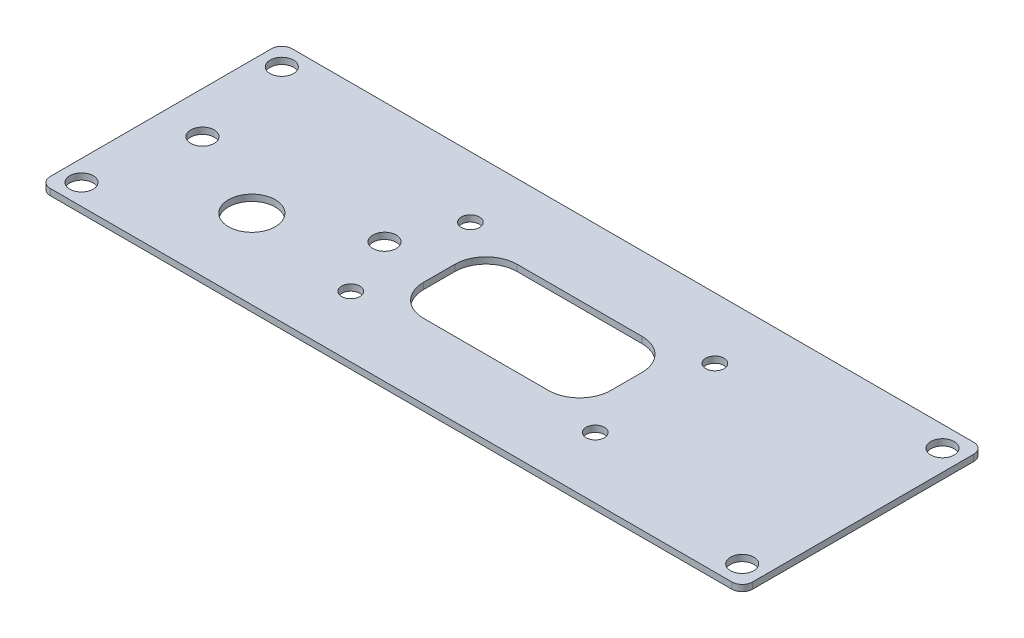
SolidWorks part; units mm, degrees
material "1023 Carbon Steel Sheet (SS)"
ref_plane "Front Plane" through (0, 0, 0) normal (0, 0, 1) x (1, 0, 0)
ref_plane "Top Plane" through (0, 0, 0) normal (0, 1, 0) x (1, 0, 0)
ref_plane "Right Plane" through (0, 0, 0) normal (1, 0, 0) x (0, 0, -1)
sketch "BASE" plane through (0, 0, 0) normal (0, 1, 0) x (1, 0, 0)
  line L0 (63.5, 19.25) -> (-63.5, 19.25) construction
  line L1 (65.5, -23.25) -> (-65.5, -23.25)
  line L2 (67.5, -21.25) -> (67.5, 21.25)
  line L3 (65.5, 23.25) -> (-65.5, 23.25)
  line L4 (-67.5, -21.25) -> (-67.5, 21.25)
  line L5 (67.5, -23.25) -> (-67.5, 23.25) construction
  line L6 (67.5, 23.25) -> (-67.5, -23.25) construction
  line L11 (27.5, 11.5) -> (-19.5, -11.5) construction
  line L12 (-19.5, 11.5) -> (27.5, -11.5) construction
  line L13 (-67.5, 0) -> (67.5, 0) construction
  line L14 (-63.5, -19.25) -> (-63.5, 19.25) construction
  line L15 (63.5, -19.25) -> (-63.5, -19.25) construction
  line L16 (63.5, -19.25) -> (63.5, 19.25) construction
  line L17 (-19.5, -11.5) -> (-19.5, 11.5) construction
  line L18 (-19.5, 11.5) -> (27.5, 11.5) construction
  line L19 (27.5, -11.5) -> (27.5, 11.5) construction
  line L20 (-19.5, -11.5) -> (27.5, -11.5) construction
  line L21 (67.5, -23.25) -> (67.5, 23.25) construction
  line L22 (67.5, -23.25) -> (-67.5, -23.25) construction
  line L23 (67.5, 23.25) -> (-67.5, 23.25) construction
  line L24 (-67.5, -23.25) -> (-67.5, 23.25) construction
  line L25 (-59.5, 0) -> (-24.5, 0) construction
  line L26 (-42, 0) -> (-42, -8) construction
  line L27 (27.5, 11.5) -> (27.5, -11.5) construction
  line L29 (34.42, -20.42) -> (57.5, -20.42) construction
  line L30 (34.42, -20.42) -> (34.42, 20.42) construction
  line L31 (34.42, 20.42) -> (57.5, 20.42) construction
  line L32 (-8, -9) -> (16, -9)
  line L33 (-14, -3) -> (-14, 3)
  line L34 (-8, 9) -> (16, 9)
  line L35 (22, -3) -> (22, 3)
  line L36 (-14, -9) -> (22, 9) construction
  line L37 (-14, 9) -> (22, -9) construction
  line L38 (57.5, -20.42) -> (57.5, 20.42) construction
  line L39 (34.42, -20.42) -> (57.5, 20.42) construction
  line L40 (34.42, 20.42) -> (57.5, -20.42) construction
  circle A0 centre (-59.5, 0) radius 2.25
  circle A1 centre (-24.5, 0) radius 2.25
  circle A6 centre (-63.5, 19.25) radius 2.25
  circle A7 centre (-63.5, -19.25) radius 2.25
  circle A8 centre (63.5, -19.25) radius 2.25
  circle A9 centre (63.5, 19.25) radius 2.25
  circle A12 centre (-19.5, 11.5) radius 1.75
  circle A13 centre (27.5, 11.5) radius 1.75
  circle A14 centre (27.5, -11.5) radius 1.75
  circle A15 centre (-19.5, -11.5) radius 1.75
  arc A16 (67.5, -21.25) -> (65.5, -23.25) centre (65.5, -21.25) cw
  arc A17 (65.5, 23.25) -> (67.5, 21.25) centre (65.5, 21.25) cw
  arc A18 (-65.5, 23.25) -> (-67.5, 21.25) centre (-65.5, 21.25) ccw
  arc A19 (-65.5, -23.25) -> (-67.5, -21.25) centre (-65.5, -21.25) cw
  circle A21 centre (-42, -8) radius 4.5
  circle A22 centre (-42, 0) radius 14 construction
  circle A23 centre (-42, -8) radius 12.7 construction
  arc A29 (-14, 3) -> (-8, 9) centre (-8, 3) cw
  arc A30 (-8, -9) -> (-14, -3) centre (-8, -3) cw
  arc A31 (16, -9) -> (22, -3) centre (16, -3) ccw
  arc A32 (22, 3) -> (16, 9) centre (16, 3) ccw
  point P0 (0, 0)
  point P6 (45.96, 0)
  point P7 (4, 0)
  point P29 (-42, 4.7)
  point P67 (4, 0)
  dimension "D6" = 4.5
  dimension "D7" = 4
  dimension "D8" = 23.08
  dimension "D9" = 40.84
  dimension "D15" = 3.5
  dimension "D16" = 2
  dimension "D17" = 9
  dimension "D19" = 28
  dimension "D20" = 25.4
  dimension "D25" = 6
  dimension "D26" = 47
  dimension "D1" = 46.5
  dimension "D2" = 135
  dimension "D3" = 18
  dimension "D4" = 4.7
  dimension "D5" = 35
  dimension "D10" = 10
  dimension "D12" = 8
  dimension "D14" = 40
  dimension "D18" = 8
  dimension "D13" = 23
  dimension "D24" = 36
extrude "SHEET" add sketch "BASE" along normal blind 1.2192
